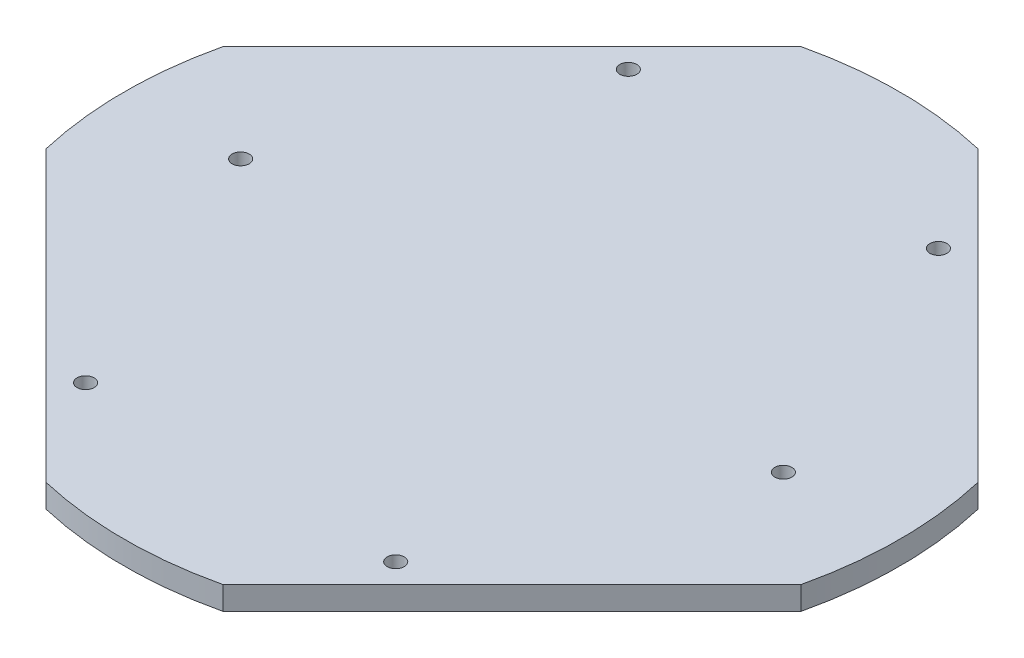
SolidWorks part; units mm, degrees
ref_plane "Front Plane" through (0, 0, 0) normal (0, 0, 1) x (1, 0, 0)
ref_plane "Top Plane" through (0, 0, 0) normal (0, 1, 0) x (1, 0, 0)
ref_plane "Right Plane" through (0, 0, 0) normal (1, 0, 0) x (0, 0, -1)
sketch "Sketch1" plane through (0, 0, 0) normal (0, 1, 0) x (1, 0, 0)
  line L2 (97.3532, -22.8549) -> (22.8549, -97.3532)
  line L3 (97.3532, 22.8549) -> (22.8549, 97.3532)
  line L4 (-22.8549, 97.3532) -> (-97.3532, 22.8549)
  line L5 (-22.8549, -97.3532) -> (-97.3532, -22.8549)
  line L6 (100, 0) -> (-100, 0) construction
  line L7 (0, 100) -> (0, -100) construction
  arc A0 (-22.8549, -97.3532) -> (22.8549, -97.3532) centre (0, 0) ccw
  arc A1 (97.3532, -22.8549) -> (97.3532, 22.8549) centre (0, 0) ccw
  arc A2 (22.8549, 97.3532) -> (-22.8549, 97.3532) centre (0, 0) ccw
  arc A4 (-97.3532, 22.8549) -> (-97.3532, -22.8549) centre (0, 0) ccw
  dimension "D2" = 200
  dimension "D1" = 170
  dimension "D3" = 170
extrude "Boss-Extrude1" add sketch "Sketch1" along normal blind 6
sketch "Sketch2" plane through (0, 6, 0) normal (0, 1, 0) x (1, 0, 0)
  line L0 (70, 0) -> (-70, 0) construction
  line L12 (-40, -70) -> (40, -70) construction
  line L17 (-40, -70) -> (-40, 70) construction
  line L19 (-40, 70) -> (40, 70) construction
  line L20 (40, -70) -> (40, 70) construction
  line L25 (-40, -70) -> (40, 70) construction
  line L31 (-40, 70) -> (40, -70) construction
  line L63 (-40, -70) -> (40, -70) construction
  circle A24 centre (-40, -70) radius 2.2
  circle A25 centre (40, -70) radius 2.2
  circle A26 centre (40, 70) radius 2.2
  circle A27 centre (-40, 70) radius 2.2
  circle A28 centre (-70, 0) radius 2.2
  circle A29 centre (70, 0) radius 2.2
  point P0 (0, 0)
  point P5 (0, 0)
  dimension "D40" = 4.4
  dimension "D42" = 4.4
  dimension "D43" = 4.4
  dimension "D46" = 4.4
  dimension "D47" = 4.4
  dimension "D1" = 4.4
  dimension "D39" = 80
  dimension "D44" = 140
  dimension "D45" = 140
extrude "Cut-Extrude1" cut sketch "Sketch2" against normal through all
